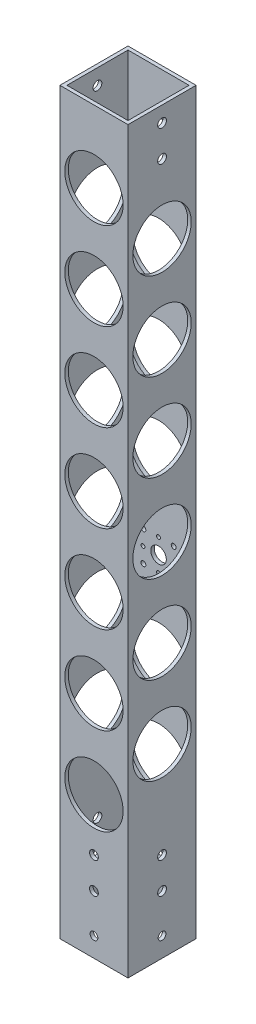
SolidWorks part; units mm, degrees
material "3003 Alloy"
ref_plane "Front Plane" through (0, 0, 0) normal (0, 0, 1) x (1, 0, 0)
ref_plane "Top Plane" through (0, 0, 0) normal (0, 1, 0) x (1, 0, 0)
ref_plane "Right Plane" through (0, 0, 0) normal (1, 0, 0) x (0, 0, -1)
sketch "Sketch1" plane through (0, 0, 0) normal (0, 1, 0) x (1, 0, 0)
  line L0 (-15.7, 0) -> (0, 0) construction
  line L1 (-15.7, 15.7) -> (15.7, 15.7)
  line L2 (-15.7, 15.7) -> (-15.7, -15.7)
  line L3 (-15.7, -15.7) -> (15.7, -15.7)
  line L4 (15.7, 15.7) -> (15.7, -15.7)
  line L5 (0, 0) -> (0, 15.7) construction
  line L6 (-17.5, 17.5) -> (17.5, 17.5)
  line L7 (17.5, 17.5) -> (17.5, -17.5)
  line L8 (-17.5, -17.5) -> (17.5, -17.5)
  line L9 (-17.5, 17.5) -> (-17.5, -17.5)
  dimension "D1" = 31.4
  dimension "D2" = 31.4
  dimension "D3" = 1.8
extrude "Boss-Extrude1" add sketch "Sketch1" along normal blind 380
sketch "Sketch3" plane through (0, 0, 17.5) normal (0, 0, 1) x (1, 0, 0)
  line L0 (17.5, 0) -> (0, 0) construction
  line L1 (0, 10) -> (0, 0) construction
  circle A0 centre (0, 10) radius 2
  dimension "D1" = 4
  dimension "D2" = 10
extrude "Cut-Extrude1" cut sketch "Sketch3" against normal through all
sketch "Sketch4" plane through (17.5, 0, 0) normal (1, 0, 0) x (0, 0, -1)
  line L0 (17.5, 0) -> (-17.5, 0) construction
  line L1 (0, 10) -> (0, 0) construction
  line L2 (-17.5, 0) -> (17.5, 0) construction
  circle A0 centre (0, 10) radius 2
  dimension "D1" = 4
  dimension "D3" = 10
extrude "Cut-Extrude2" cut sketch "Sketch4" against normal through all
sketch "Sketch13" plane through (-17.5, 0, 0) normal (-1, 0, 0) x (0, 0, 1)
  line L0 (-17.5, 95.5) -> (17.5, 95.5) construction
  line L1 (-17.5, 380) -> (-17.5, 0) construction
  line L2 (17.5, 380) -> (17.5, 0) construction
  line L3 (-17.5, 0) -> (17.5, 0) construction
  circle A0 centre (0, 95.5) radius 15
  dimension "D1" = 30
  dimension "D2" = 95.5
extrude "Cut-Extrude10" cut sketch "Sketch13" against normal through all
sketch "Sketch14" plane through (17.5, 0, 0) normal (1, 0, 0) x (0, 0, -1)
  line L0 (0, 380) -> (0, 372) construction
  line L1 (-17.5, 380) -> (17.5, 380) construction
  line L2 (0, 372) -> (0, 356) construction
  line L3 (0, 30) -> (0, 0) construction
  line L4 (0, 46) -> (0, 30) construction
  circle A0 centre (0, 372) radius 2.25
  circle A1 centre (0, 356) radius 2.25
  circle A2 centre (0, 46) radius 2.25
  circle A3 centre (0, 30) radius 2.25
  dimension "D2" = 4.5
  dimension "D5" = 4.5
  dimension "D1" = 16
  dimension "D3" = 8
  dimension "D4" = 16
  dimension "D6" = 30
extrude "Cut-Extrude11" cut sketch "Sketch14" against normal through all
pattern_linear "LPattern1" count 6 spacing 45 along (0, 1, 0) of "Cut-Extrude10"
sketch "Sketch16" plane through (0, 0, 17.5) normal (0, 0, 1) x (1, 0, 0)
  line L0 (0, 0) -> (0, 30) construction
  line L1 (-17.5, 0) -> (17.5, 0) construction
  line L2 (0, 30) -> (0, 46) construction
  circle A0 centre (0, 46) radius 2.25
  circle A1 centre (0, 30) radius 2.25
  dimension "D1" = 4.5
  dimension "D2" = 16
  dimension "D3" = 30
extrude "Cut-Extrude13" cut sketch "Sketch16" against normal through all
sketch "Sketch17" plane through (0, 0, 17.5) normal (0, 0, 1) x (1, 0, 0)
  line L0 (0, 73) -> (0, 0) construction
  line L1 (-17.5, 0) -> (17.5, 0) construction
  circle A0 centre (0, 73) radius 15
  dimension "D1" = 30
  dimension "D2" = 73
extrude "Cut-Extrude14" cut sketch "Sketch17" against normal through all
pattern_linear "LPattern2" count 7 spacing 45 along (0, 1, 0) of "Cut-Extrude14"
sketch "Sketch18" plane through (0, 0, -17.5) normal (0, 0, -1) x (-1, 0, 0)
  circle A0 centre (0, 163) radius 15
  circle A1 centre (0, 163) radius 15 construction
extrude "Boss-Extrude2" add sketch "Sketch18" against normal up to surface (1.8 mm away) up to face at (15, 118, -15.7)
sketch "Sketch19" plane through (0, 0, -15.7) normal (0, 0, 1) x (1, 0, 0)
  circle A0 centre (0, 163) radius 4
  dimension "D1" = 8
extrude "Cut-Extrude15" cut sketch "Sketch19" against normal through all
sketch "Sketch20" plane through (0, 0, -17.5) normal (0, 0, -1) x (-1, 0, 0)
  circle A0 centre (0, 171) radius 1
  circle A1 centre (0, 155) radius 1
  circle A2 centre (8, 163) radius 1
  circle A3 centre (-8, 163) radius 1
  circle A4 centre (-7.7782, 155.2218) radius 1.25
  circle A5 centre (7.7782, 155.2218) radius 1.25
  circle A6 centre (7.7782, 170.7782) radius 1.25
  circle A7 centre (-7.7782, 170.7782) radius 1.25
  dimension "D1" = 2
  dimension "D2" = 2.5
extrude "Cut-Extrude16" cut sketch "Sketch20" against normal up to next
